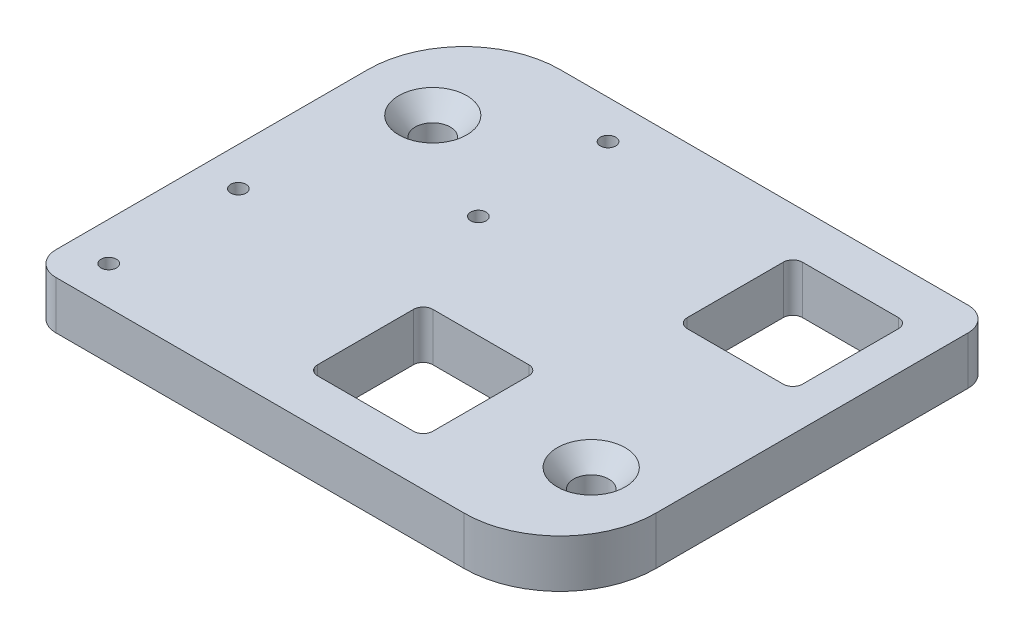
SolidWorks part; units mm, degrees
ref_plane "Top" through (0, 0, 0) normal (0, 0, 1) x (1, 0, 0)
ref_plane "Front" through (0, 0, 0) normal (0, 1, 0) x (1, 0, 0)
ref_plane "Right" through (0, 0, 0) normal (1, 0, 0) x (0, 0, -1)
sketch "Base Sketch" plane through (0, 0, 0) normal (0, 1, 0) x (1, 0, 0)
  line L1 (-27.5, 45) -> (27.5, 45)
  line L2 (-27.5, 45) -> (-27.5, 0)
  line L3 (-27.5, 0) -> (27.5, 0)
  line L4 (27.5, 45) -> (27.5, 0)
  dimension "D1" = 55
  dimension "D2" = 45
extrude "Base Extrude" add sketch "Base Sketch" against normal blind 5
hole_wizard "Mosfet Mounting Holes" positions "Mosfet Mounting Holes Position Sketch" profile "Mosfet Mounting Holes Profile Sketch" hole size "M2x0.4" standard "ANSI Metric" end condition through all
sketch "Mosfet Mounting Holes Position Sketch" plane through (0, 0, 0) normal (0, 1, 0) x (1, 0, 0)
  line L0 (-23.5, 17.5) -> (-23.5, 4) construction
  line L2 (-8.5, 41) -> (-8.5, 27.5) construction
  line L4 (-27.5, 45) -> (-27.5, 0) construction
  line L5 (-27.5, 0) -> (27.5, 0) construction
  line L6 (27.5, 45) -> (-27.5, 45) construction
  line L7 (27.5, 0) -> (27.5, 45) construction
  point P0 (-23.5, 4)
  point P2 (-23.5, 17.5)
  point P4 (-8.5, 27.5)
  point P6 (-8.5, 41)
  dimension "D1" = 13.5
  dimension "D2" = 36
sketch "Mosfet Mounting Holes Profile Sketch" plane through (-23.5, 0, -4) normal (1, 0, 0) x (0, 0, 1)
  line L0 (0, 0) -> (0, 5)
  line L1 (0, 5) -> (0.8, 5)
  line L2 (0.8, 5) -> (0.8, 0)
  line L5 (0.8, 0) -> (0, 0)
  line L11 (0, -6.35) -> (0, 107.95) construction
  dimension "Thru Hole Dia." = 1.6
  dimension "Thru Hole Depth" = 5
hole_wizard "Mounting Holes" positions "Mounting Holes Position Sketch" profile "Mounting Hole Profile Sketch" countersink size "#6" standard "ANSI Inch" end condition through all
sketch "Mounting Holes Position Sketch" plane through (0, 0, 0) normal (0, 1, 0) x (1, 0, 0)
  line L0 (-27.5, 34.25) -> (-8.5, 34.25) construction
  line L2 (-8.5, 41) -> (-8.5, 27.5) construction
  line L3 (-23.5, 10.75) -> (27.5, 10.75) construction
  line L5 (-23.5, 17.5) -> (-23.5, 4) construction
  line L7 (-27.5, 45) -> (-27.5, 0) construction
  line L8 (27.5, 0) -> (27.5, 45) construction
  point P0 (-20, 34.25)
  point P2 (20, 10.75)
sketch "Mounting Hole Profile Sketch" plane through (-20, 0, -34.25) normal (1, 0, 0) x (0, 0, 1)
  line L0 (0, 0) -> (0, 5)
  line L1 (0, 5) -> (1.8288, 5)
  line L2 (1.8288, 5) -> (1.8288, 1.9723)
  line L3 (1.8288, 1.9723) -> (3.5433, 0)
  line L5 (3.5433, 0) -> (0, 0)
  line L6 (-1.8288, 1.9723) -> (-3.5433, 0) construction
  line L11 (0, -6.35) -> (0, 107.95) construction
  dimension "Thru Hole Dia." = 3.6576
  dimension "Thru Hole Depth" = 5
  dimension "Near C'Sink Dia." = 7.0866
  dimension "Near C'Sink Angle" = 82
sketch "Pin Relief Sketch" plane through (0, 0, 0) normal (0, 1, 0) x (1, 0, 0)
  line L0 (-23.5, 17.5) -> (-23.5, 4) construction
  line L1 (-3.5, 16.75) -> (8.5, 16.75)
  line L2 (-3.5, 16.75) -> (-3.5, 4.75)
  line L3 (-3.5, 4.75) -> (8.5, 4.75)
  line L4 (8.5, 16.75) -> (8.5, 4.75)
  line L5 (-23.5, 10.75) -> (-3.5, 10.75) construction
  line L6 (-8.5, 34.25) -> (11.5, 34.25) construction
  line L7 (-8.5, 41) -> (-8.5, 27.5) construction
  line L8 (11.5, 40.25) -> (23.5, 40.25)
  line L9 (11.5, 40.25) -> (11.5, 28.25)
  line L10 (11.5, 28.25) -> (23.5, 28.25)
  line L11 (23.5, 40.25) -> (23.5, 28.25)
  dimension "D1" = 12
  dimension "D2" = 20
  dimension "D3" = 12
extrude "Cut Termal Pin Relief" cut sketch "Pin Relief Sketch" against normal through all
fillet "Fillet1" radius 10 2 edges at (-27.5, -2.5, -45) (27.5, -2.5, 0)
fillet "Fillet2" radius 2.5 2 edges at (-27.5, -2.5, 0) (27.5, -2.5, -45)
fillet "Fillet3" radius 1 8 edges at (8.5, -2.5, -16.75) (-3.5, -2.5, -16.75) (-3.5, -2.5, -4.75) (8.5, -2.5, -4.75) (23.5, -2.5, -28.25) (11.5, -2.5, -28.25) (11.5, -2.5, -40.25) (23.5, -2.5, -40.25)
